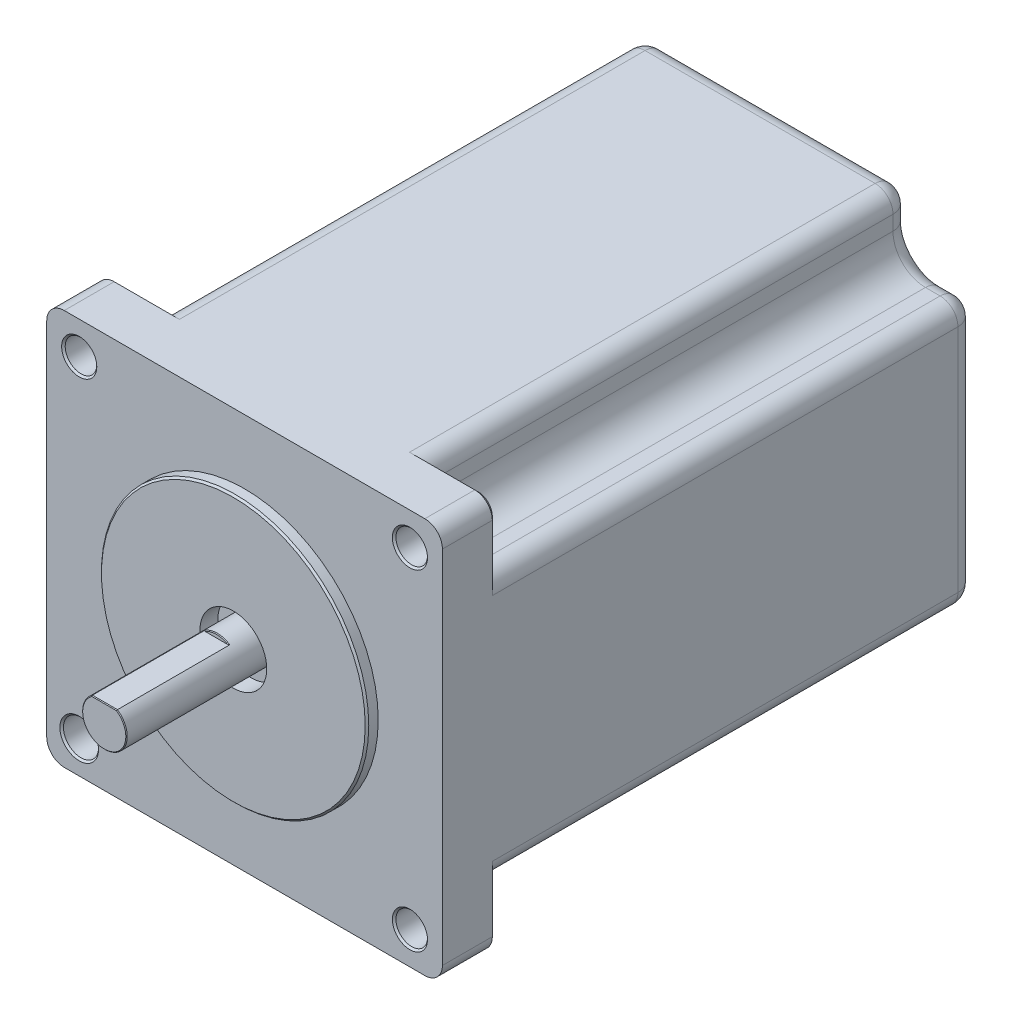
SolidWorks part; units mm, degrees
ref_plane "Front Plane" through (0, 0, 0) normal (0, 0, 1) x (1, 0, 0)
ref_plane "Top Plane" through (0, 0, 0) normal (0, 1, 0) x (1, 0, 0)
ref_plane "Right Plane" through (0, 0, 0) normal (1, 0, 0) x (0, 0, -1)
sketch "Sketch1" plane through (0, 0, 0) normal (0, 0, 1) x (1, 0, 0)
  line L0 (25.7, -28.2) -> (-25.7, -28.2)
  line L1 (-28.2, -25.7) -> (-28.2, 25.7)
  line L2 (-25.7, 28.2) -> (25.7, 28.2)
  line L3 (28.2, 25.7) -> (28.2, -25.7)
  line L4 (10.4502, 28.2) -> (10.4502, 25.35)
  line L5 (16.7502, 28.2) -> (16.7502, 25.35)
  line L6 (-10.4502, -28.2) -> (-10.4502, -25.35)
  line L7 (-16.7502, -28.2) -> (-16.7502, -25.35)
  line L8 (24.8128, -14.6733) -> (25.354, -14.1321)
  line L9 (24.2796, -14.1427) -> (24.8181, -13.6042)
  line L10 (28.2, -16.7502) -> (25.35, -16.7502)
  line L11 (23.8824, -14.8147) -> (24.1419, -15.0742)
  line L12 (28.2, -10.4502) -> (25.35, -10.4502)
  line L13 (-28.2, 16.7502) -> (-25.35, 16.7502)
  line L14 (-28.2, 10.4502) -> (-25.35, 10.4502)
  line L15 (26.4231, -14.1374) -> (25.8819, -13.5962)
  line L16 (25.8925, -14.6706) -> (25.354, -14.1321)
  line L17 (26.5644, -15.0678) -> (26.824, -14.8083)
  line L18 (25.8872, -12.5271) -> (25.346, -13.0683)
  line L19 (26.4204, -13.0577) -> (25.8819, -13.5962)
  line L20 (26.8176, -12.3858) -> (26.5581, -12.1262)
  line L21 (24.2769, -13.063) -> (24.8181, -13.6042)
  line L22 (24.8075, -12.5298) -> (25.346, -13.0683)
  line L23 (24.1356, -12.1326) -> (23.876, -12.3921)
  line L24 (-14.1374, -26.4231) -> (-13.5962, -25.8819)
  line L25 (-14.6706, -25.8925) -> (-14.1321, -25.354)
  line L26 (-15.0678, -26.5644) -> (-14.8083, -26.824)
  line L27 (-12.5271, -25.8872) -> (-13.0683, -25.346)
  line L28 (-13.0577, -26.4204) -> (-13.5962, -25.8819)
  line L29 (-12.3858, -26.8176) -> (-12.1262, -26.5581)
  line L30 (-13.063, -24.2769) -> (-13.6042, -24.8181)
  line L31 (-12.5298, -24.8075) -> (-13.0683, -25.346)
  line L32 (-12.1326, -24.1356) -> (-12.3921, -23.876)
  line L33 (-14.6733, -24.8128) -> (-14.1321, -25.354)
  line L34 (-14.1427, -24.2796) -> (-13.6042, -24.8181)
  line L35 (-14.8147, -23.8824) -> (-15.0742, -24.1419)
  line L36 (-25.8872, 12.5271) -> (-25.346, 13.0683)
  line L37 (-26.4204, 13.0577) -> (-25.8819, 13.5962)
  line L38 (-26.8176, 12.3858) -> (-26.5581, 12.1262)
  line L39 (-24.2769, 13.063) -> (-24.8181, 13.6042)
  line L40 (-24.8075, 12.5298) -> (-25.346, 13.0683)
  line L41 (-24.1356, 12.1326) -> (-23.876, 12.3921)
  line L42 (-24.8128, 14.6733) -> (-25.354, 14.1321)
  line L43 (-24.2796, 14.1427) -> (-24.8181, 13.6042)
  line L44 (-23.8824, 14.8147) -> (-24.1419, 15.0742)
  line L45 (-26.4231, 14.1374) -> (-25.8819, 13.5962)
  line L46 (-25.8925, 14.6706) -> (-25.354, 14.1321)
  line L47 (-26.5644, 15.0678) -> (-26.824, 14.8083)
  line L48 (13.063, 24.2769) -> (13.6042, 24.8181)
  line L49 (12.5298, 24.8075) -> (13.0683, 25.346)
  line L50 (12.1326, 24.1356) -> (12.3921, 23.876)
  line L51 (14.6733, 24.8128) -> (14.1321, 25.354)
  line L52 (14.1427, 24.2796) -> (13.6042, 24.8181)
  line L53 (14.8147, 23.8824) -> (15.0742, 24.1419)
  line L54 (14.1374, 26.4231) -> (13.5962, 25.8819)
  line L55 (14.6706, 25.8925) -> (14.1321, 25.354)
  line L56 (15.0678, 26.5644) -> (14.8083, 26.824)
  line L57 (12.5271, 25.8872) -> (13.0683, 25.346)
  line L58 (13.0577, 26.4204) -> (13.5962, 25.8819)
  line L59 (12.3858, 26.8176) -> (12.1262, 26.5581)
  line L60 (2.6694, -1.7014) -> (2.6694, 1.7574)
  line L61 (2.4712, -1.6418) -> (2.4712, 1.6978)
  line L62 (-5.066, -28.2) -> (5.066, -28.2)
  line L63 (5.066, -28.2) -> (5.938, -27.328)
  line L64 (-5.066, -28.2) -> (-5.938, -27.328)
  circle A0 centre (0, 0) radius 27.7884
  circle A1 centre (13.6002, 25.35) radius 2.2554
  arc A2 (-25.7, 28.2) -> (-28.2, 25.7) centre (-25.7, 25.7) ccw
  arc A3 (-28.2, -25.7) -> (-25.7, -28.2) centre (-25.7, -25.7) ccw
  arc A4 (25.7, -28.2) -> (28.2, -25.7) centre (25.7, -25.7) ccw
  arc A5 (28.2, 25.7) -> (25.7, 28.2) centre (25.7, 25.7) ccw
  circle A6 centre (-23.57, 23.57) radius 2.25
  circle A7 centre (23.57, 23.57) radius 2.25
  circle A8 centre (23.57, -23.57) radius 2.25
  arc A9 (10.4502, 25.35) -> (16.7502, 25.35) centre (13.6002, 25.35) ccw
  arc A10 (-10.4502, -25.35) -> (-16.7502, -25.35) centre (-13.6002, -25.35) ccw
  circle A11 centre (-13.6002, -25.35) radius 2.2554
  circle A12 centre (25.35, -13.6002) radius 2.2554
  arc A13 (25.35, -10.4502) -> (25.35, -16.7502) centre (25.35, -13.6002) ccw
  circle A14 centre (-25.35, 13.6002) radius 2.2554
  arc A15 (-25.35, 10.4502) -> (-25.35, 16.7502) centre (-25.35, 13.6002) ccw
  circle A16 centre (0, 0) radius 19.05
  arc A17 (2.6694, 1.7574) -> (2.6694, -1.7014) centre (0, 0.028) ccw
  circle A18 centre (-23.57, -23.57) radius 2.5
  arc A19 (24.2796, -14.1427) -> (23.8824, -14.8147) centre (25.548, -15.3459) ccw
  arc A20 (24.1419, -15.0742) -> (24.8128, -14.6733) centre (23.6033, -13.4109) ccw
  arc A21 (25.8925, -14.6706) -> (26.5644, -15.0678) centre (27.0957, -13.4022) ccw
  arc A22 (26.824, -14.8083) -> (26.4231, -14.1374) centre (25.1607, -15.3469) ccw
  arc A23 (26.4204, -13.0577) -> (26.8176, -12.3858) centre (25.152, -11.8545) ccw
  arc A24 (26.5581, -12.1262) -> (25.8872, -12.5271) centre (27.0967, -13.7895) ccw
  arc A25 (24.8075, -12.5298) -> (24.1356, -12.1326) centre (23.6043, -13.7982) ccw
  arc A26 (23.876, -12.3921) -> (24.2769, -13.063) centre (25.5393, -11.8535) ccw
  arc A27 (-14.6706, -25.8925) -> (-15.0678, -26.5644) centre (-13.4022, -27.0957) ccw
  arc A28 (-14.8083, -26.824) -> (-14.1374, -26.4231) centre (-15.3469, -25.1607) ccw
  arc A29 (-13.0577, -26.4204) -> (-12.3858, -26.8176) centre (-11.8545, -25.152) ccw
  arc A30 (-12.1262, -26.5581) -> (-12.5271, -25.8872) centre (-13.7895, -27.0967) ccw
  arc A31 (-12.5298, -24.8075) -> (-12.1326, -24.1356) centre (-13.7982, -23.6043) ccw
  arc A32 (-12.3921, -23.876) -> (-13.063, -24.2769) centre (-11.8535, -25.5393) ccw
  arc A33 (-14.1427, -24.2796) -> (-14.8147, -23.8824) centre (-15.3459, -25.548) ccw
  arc A34 (-15.0742, -24.1419) -> (-14.6733, -24.8128) centre (-13.4109, -23.6033) ccw
  arc A35 (-26.4204, 13.0577) -> (-26.8176, 12.3858) centre (-25.152, 11.8545) ccw
  arc A36 (-26.5581, 12.1262) -> (-25.8872, 12.5271) centre (-27.0967, 13.7895) ccw
  arc A37 (-24.8075, 12.5298) -> (-24.1356, 12.1326) centre (-23.6043, 13.7982) ccw
  arc A38 (-23.876, 12.3921) -> (-24.2769, 13.063) centre (-25.5393, 11.8535) ccw
  arc A39 (-24.2796, 14.1427) -> (-23.8824, 14.8147) centre (-25.548, 15.3459) ccw
  arc A40 (-24.1419, 15.0742) -> (-24.8128, 14.6733) centre (-23.6033, 13.4109) ccw
  arc A41 (-25.8925, 14.6706) -> (-26.5644, 15.0678) centre (-27.0957, 13.4022) ccw
  arc A42 (-26.824, 14.8083) -> (-26.4231, 14.1374) centre (-25.1607, 15.3469) ccw
  arc A43 (12.5298, 24.8075) -> (12.1326, 24.1356) centre (13.7982, 23.6043) ccw
  arc A44 (12.3921, 23.876) -> (13.063, 24.2769) centre (11.8535, 25.5393) ccw
  arc A45 (14.1427, 24.2796) -> (14.8147, 23.8824) centre (15.3459, 25.548) ccw
  arc A46 (15.0742, 24.1419) -> (14.6733, 24.8128) centre (13.4109, 23.6033) ccw
  arc A47 (14.6706, 25.8925) -> (15.0678, 26.5644) centre (13.4022, 27.0957) ccw
  arc A48 (14.8083, 26.824) -> (14.1374, 26.4231) centre (15.3469, 25.1607) ccw
  arc A49 (13.0577, 26.4204) -> (12.3858, 26.8176) centre (11.8545, 25.152) ccw
  arc A50 (12.1262, 26.5581) -> (12.5271, 25.8872) centre (13.7895, 27.0967) ccw
  circle A51 centre (0, 0) radius 4.5332
  arc A52 (2.4712, 1.6978) -> (2.4712, -1.6418) centre (0, 0.028) ccw
extrude "Extrude1" add sketch "Sketch1" along normal blind 7.62 contours L2 A5 L3 A4 L0 A3 L1 A2
sketch "Sketch2" plane through (0, 0, 7.62) normal (0, 0, 1) x (1, 0, 0)
  line L0 (25.7, -28.2) -> (-25.7, -28.2)
  line L1 (-28.2, -25.7) -> (-28.2, 25.7)
  line L2 (-25.7, 28.2) -> (25.7, 28.2)
  line L3 (28.2, 25.7) -> (28.2, -25.7)
  line L4 (10.4502, 28.2) -> (10.4502, 25.35)
  line L5 (16.7502, 28.2) -> (16.7502, 25.35)
  line L6 (-10.4502, -28.2) -> (-10.4502, -25.35)
  line L7 (-16.7502, -28.2) -> (-16.7502, -25.35)
  line L8 (24.8128, -14.6733) -> (25.354, -14.1321)
  line L9 (24.2796, -14.1427) -> (24.8181, -13.6042)
  line L10 (28.2, -16.7502) -> (25.35, -16.7502)
  line L11 (23.8824, -14.8147) -> (24.1419, -15.0742)
  line L12 (28.2, -10.4502) -> (25.35, -10.4502)
  line L13 (-28.2, 16.7502) -> (-25.35, 16.7502)
  line L14 (-28.2, 10.4502) -> (-25.35, 10.4502)
  line L15 (26.4231, -14.1374) -> (25.8819, -13.5962)
  line L16 (25.8925, -14.6706) -> (25.354, -14.1321)
  line L17 (26.5644, -15.0678) -> (26.824, -14.8083)
  line L18 (25.8872, -12.5271) -> (25.346, -13.0683)
  line L19 (26.4204, -13.0577) -> (25.8819, -13.5962)
  line L20 (26.8176, -12.3858) -> (26.5581, -12.1262)
  line L21 (24.2769, -13.063) -> (24.8181, -13.6042)
  line L22 (24.8075, -12.5298) -> (25.346, -13.0683)
  line L23 (24.1356, -12.1326) -> (23.876, -12.3921)
  line L24 (-14.1374, -26.4231) -> (-13.5962, -25.8819)
  line L25 (-14.6706, -25.8925) -> (-14.1321, -25.354)
  line L26 (-15.0678, -26.5644) -> (-14.8083, -26.824)
  line L27 (-12.5271, -25.8872) -> (-13.0683, -25.346)
  line L28 (-13.0577, -26.4204) -> (-13.5962, -25.8819)
  line L29 (-12.3858, -26.8176) -> (-12.1262, -26.5581)
  line L30 (-13.063, -24.2769) -> (-13.6042, -24.8181)
  line L31 (-12.5298, -24.8075) -> (-13.0683, -25.346)
  line L32 (-12.1326, -24.1356) -> (-12.3921, -23.876)
  line L33 (-14.6733, -24.8128) -> (-14.1321, -25.354)
  line L34 (-14.1427, -24.2796) -> (-13.6042, -24.8181)
  line L35 (-14.8147, -23.8824) -> (-15.0742, -24.1419)
  line L36 (-25.8872, 12.5271) -> (-25.346, 13.0683)
  line L37 (-26.4204, 13.0577) -> (-25.8819, 13.5962)
  line L38 (-26.8176, 12.3858) -> (-26.5581, 12.1262)
  line L39 (-24.2769, 13.063) -> (-24.8181, 13.6042)
  line L40 (-24.8075, 12.5298) -> (-25.346, 13.0683)
  line L41 (-24.1356, 12.1326) -> (-23.876, 12.3921)
  line L42 (-24.8128, 14.6733) -> (-25.354, 14.1321)
  line L43 (-24.2796, 14.1427) -> (-24.8181, 13.6042)
  line L44 (-23.8824, 14.8147) -> (-24.1419, 15.0742)
  line L45 (-26.4231, 14.1374) -> (-25.8819, 13.5962)
  line L46 (-25.8925, 14.6706) -> (-25.354, 14.1321)
  line L47 (-26.5644, 15.0678) -> (-26.824, 14.8083)
  line L48 (13.063, 24.2769) -> (13.6042, 24.8181)
  line L49 (12.5298, 24.8075) -> (13.0683, 25.346)
  line L50 (12.1326, 24.1356) -> (12.3921, 23.876)
  line L51 (14.6733, 24.8128) -> (14.1321, 25.354)
  line L52 (14.1427, 24.2796) -> (13.6042, 24.8181)
  line L53 (14.8147, 23.8824) -> (15.0742, 24.1419)
  line L54 (14.1374, 26.4231) -> (13.5962, 25.8819)
  line L55 (14.6706, 25.8925) -> (14.1321, 25.354)
  line L56 (15.0678, 26.5644) -> (14.8083, 26.824)
  line L57 (12.5271, 25.8872) -> (13.0683, 25.346)
  line L58 (13.0577, 26.4204) -> (13.5962, 25.8819)
  line L59 (12.3858, 26.8176) -> (12.1262, 26.5581)
  line L60 (2.6694, -1.7014) -> (2.6694, 1.7574)
  line L61 (2.4712, -1.6418) -> (2.4712, 1.6978)
  line L62 (-5.066, -28.2) -> (5.066, -28.2)
  line L63 (5.066, -28.2) -> (5.938, -27.328)
  line L64 (-5.066, -28.2) -> (-5.938, -27.328)
  circle A0 centre (13.6002, 25.35) radius 2.2554
  arc A1 (-25.7, 28.2) -> (-28.2, 25.7) centre (-25.7, 25.7) ccw
  arc A2 (-28.2, -25.7) -> (-25.7, -28.2) centre (-25.7, -25.7) ccw
  arc A3 (25.7, -28.2) -> (28.2, -25.7) centre (25.7, -25.7) ccw
  arc A4 (28.2, 25.7) -> (25.7, 28.2) centre (25.7, 25.7) ccw
  circle A5 centre (-23.57, 23.57) radius 2.25
  circle A6 centre (23.57, 23.57) radius 2.25
  circle A7 centre (23.57, -23.57) radius 2.25
  arc A8 (10.4502, 25.35) -> (16.7502, 25.35) centre (13.6002, 25.35) ccw
  arc A9 (-10.4502, -25.35) -> (-16.7502, -25.35) centre (-13.6002, -25.35) ccw
  circle A10 centre (-13.6002, -25.35) radius 2.2554
  circle A11 centre (25.35, -13.6002) radius 2.2554
  arc A12 (25.35, -10.4502) -> (25.35, -16.7502) centre (25.35, -13.6002) ccw
  circle A13 centre (-25.35, 13.6002) radius 2.2554
  arc A14 (-25.35, 10.4502) -> (-25.35, 16.7502) centre (-25.35, 13.6002) ccw
  circle A15 centre (0, 0) radius 19.05
  arc A16 (2.6694, 1.7574) -> (2.6694, -1.7014) centre (0, 0.028) ccw
  circle A17 centre (-23.57, -23.57) radius 2.5
  arc A18 (24.2796, -14.1427) -> (23.8824, -14.8147) centre (25.548, -15.3459) ccw
  arc A19 (24.1419, -15.0742) -> (24.8128, -14.6733) centre (23.6033, -13.4109) ccw
  arc A20 (25.8925, -14.6706) -> (26.5644, -15.0678) centre (27.0957, -13.4022) ccw
  arc A21 (26.824, -14.8083) -> (26.4231, -14.1374) centre (25.1607, -15.3469) ccw
  arc A22 (26.4204, -13.0577) -> (26.8176, -12.3858) centre (25.152, -11.8545) ccw
  arc A23 (26.5581, -12.1262) -> (25.8872, -12.5271) centre (27.0967, -13.7895) ccw
  arc A24 (24.8075, -12.5298) -> (24.1356, -12.1326) centre (23.6043, -13.7982) ccw
  arc A25 (23.876, -12.3921) -> (24.2769, -13.063) centre (25.5393, -11.8535) ccw
  arc A26 (-14.6706, -25.8925) -> (-15.0678, -26.5644) centre (-13.4022, -27.0957) ccw
  arc A27 (-14.8083, -26.824) -> (-14.1374, -26.4231) centre (-15.3469, -25.1607) ccw
  arc A28 (-13.0577, -26.4204) -> (-12.3858, -26.8176) centre (-11.8545, -25.152) ccw
  arc A29 (-12.1262, -26.5581) -> (-12.5271, -25.8872) centre (-13.7895, -27.0967) ccw
  arc A30 (-12.5298, -24.8075) -> (-12.1326, -24.1356) centre (-13.7982, -23.6043) ccw
  arc A31 (-12.3921, -23.876) -> (-13.063, -24.2769) centre (-11.8535, -25.5393) ccw
  arc A32 (-14.1427, -24.2796) -> (-14.8147, -23.8824) centre (-15.3459, -25.548) ccw
  arc A33 (-15.0742, -24.1419) -> (-14.6733, -24.8128) centre (-13.4109, -23.6033) ccw
  arc A34 (-26.4204, 13.0577) -> (-26.8176, 12.3858) centre (-25.152, 11.8545) ccw
  arc A35 (-26.5581, 12.1262) -> (-25.8872, 12.5271) centre (-27.0967, 13.7895) ccw
  arc A36 (-24.8075, 12.5298) -> (-24.1356, 12.1326) centre (-23.6043, 13.7982) ccw
  arc A37 (-23.876, 12.3921) -> (-24.2769, 13.063) centre (-25.5393, 11.8535) ccw
  arc A38 (-24.2796, 14.1427) -> (-23.8824, 14.8147) centre (-25.548, 15.3459) ccw
  arc A39 (-24.1419, 15.0742) -> (-24.8128, 14.6733) centre (-23.6033, 13.4109) ccw
  arc A40 (-25.8925, 14.6706) -> (-26.5644, 15.0678) centre (-27.0957, 13.4022) ccw
  arc A41 (-26.824, 14.8083) -> (-26.4231, 14.1374) centre (-25.1607, 15.3469) ccw
  arc A42 (12.5298, 24.8075) -> (12.1326, 24.1356) centre (13.7982, 23.6043) ccw
  arc A43 (12.3921, 23.876) -> (13.063, 24.2769) centre (11.8535, 25.5393) ccw
  arc A44 (14.1427, 24.2796) -> (14.8147, 23.8824) centre (15.3459, 25.548) ccw
  arc A45 (15.0742, 24.1419) -> (14.6733, 24.8128) centre (13.4109, 23.6033) ccw
  arc A46 (14.6706, 25.8925) -> (15.0678, 26.5644) centre (13.4022, 27.0957) ccw
  arc A47 (14.8083, 26.824) -> (14.1374, 26.4231) centre (15.3469, 25.1607) ccw
  arc A48 (13.0577, 26.4204) -> (12.3858, 26.8176) centre (11.8545, 25.152) ccw
  arc A49 (12.1262, 26.5581) -> (12.5271, 25.8872) centre (13.7895, 27.0967) ccw
  circle A50 centre (0, 0) radius 4.5332
  arc A51 (2.4712, 1.6978) -> (2.4712, -1.6418) centre (0, 0.028) ccw
extrude "Extrude2" cut sketch "Sketch2" against normal blind 7.62 contours A5
sketch "Sketch3" plane through (0, 0, 7.62) normal (0, 0, 1) x (1, 0, 0)
  line L0 (25.7, -28.2) -> (-25.7, -28.2)
  line L1 (-28.2, -25.7) -> (-28.2, 25.7)
  line L2 (-25.7, 28.2) -> (25.7, 28.2)
  line L3 (28.2, 25.7) -> (28.2, -25.7)
  line L4 (10.4502, 28.2) -> (10.4502, 25.35)
  line L5 (16.7502, 28.2) -> (16.7502, 25.35)
  line L6 (-10.4502, -28.2) -> (-10.4502, -25.35)
  line L7 (-16.7502, -28.2) -> (-16.7502, -25.35)
  line L8 (24.8128, -14.6733) -> (25.354, -14.1321)
  line L9 (24.2796, -14.1427) -> (24.8181, -13.6042)
  line L10 (28.2, -16.7502) -> (25.35, -16.7502)
  line L11 (23.8824, -14.8147) -> (24.1419, -15.0742)
  line L12 (28.2, -10.4502) -> (25.35, -10.4502)
  line L13 (-28.2, 16.7502) -> (-25.35, 16.7502)
  line L14 (-28.2, 10.4502) -> (-25.35, 10.4502)
  line L15 (26.4231, -14.1374) -> (25.8819, -13.5962)
  line L16 (25.8925, -14.6706) -> (25.354, -14.1321)
  line L17 (26.5644, -15.0678) -> (26.824, -14.8083)
  line L18 (25.8872, -12.5271) -> (25.346, -13.0683)
  line L19 (26.4204, -13.0577) -> (25.8819, -13.5962)
  line L20 (26.8176, -12.3858) -> (26.5581, -12.1262)
  line L21 (24.2769, -13.063) -> (24.8181, -13.6042)
  line L22 (24.8075, -12.5298) -> (25.346, -13.0683)
  line L23 (24.1356, -12.1326) -> (23.876, -12.3921)
  line L24 (-14.1374, -26.4231) -> (-13.5962, -25.8819)
  line L25 (-14.6706, -25.8925) -> (-14.1321, -25.354)
  line L26 (-15.0678, -26.5644) -> (-14.8083, -26.824)
  line L27 (-12.5271, -25.8872) -> (-13.0683, -25.346)
  line L28 (-13.0577, -26.4204) -> (-13.5962, -25.8819)
  line L29 (-12.3858, -26.8176) -> (-12.1262, -26.5581)
  line L30 (-13.063, -24.2769) -> (-13.6042, -24.8181)
  line L31 (-12.5298, -24.8075) -> (-13.0683, -25.346)
  line L32 (-12.1326, -24.1356) -> (-12.3921, -23.876)
  line L33 (-14.6733, -24.8128) -> (-14.1321, -25.354)
  line L34 (-14.1427, -24.2796) -> (-13.6042, -24.8181)
  line L35 (-14.8147, -23.8824) -> (-15.0742, -24.1419)
  line L36 (-25.8872, 12.5271) -> (-25.346, 13.0683)
  line L37 (-26.4204, 13.0577) -> (-25.8819, 13.5962)
  line L38 (-26.8176, 12.3858) -> (-26.5581, 12.1262)
  line L39 (-24.2769, 13.063) -> (-24.8181, 13.6042)
  line L40 (-24.8075, 12.5298) -> (-25.346, 13.0683)
  line L41 (-24.1356, 12.1326) -> (-23.876, 12.3921)
  line L42 (-24.8128, 14.6733) -> (-25.354, 14.1321)
  line L43 (-24.2796, 14.1427) -> (-24.8181, 13.6042)
  line L44 (-23.8824, 14.8147) -> (-24.1419, 15.0742)
  line L45 (-26.4231, 14.1374) -> (-25.8819, 13.5962)
  line L46 (-25.8925, 14.6706) -> (-25.354, 14.1321)
  line L47 (-26.5644, 15.0678) -> (-26.824, 14.8083)
  line L48 (13.063, 24.2769) -> (13.6042, 24.8181)
  line L49 (12.5298, 24.8075) -> (13.0683, 25.346)
  line L50 (12.1326, 24.1356) -> (12.3921, 23.876)
  line L51 (14.6733, 24.8128) -> (14.1321, 25.354)
  line L52 (14.1427, 24.2796) -> (13.6042, 24.8181)
  line L53 (14.8147, 23.8824) -> (15.0742, 24.1419)
  line L54 (14.1374, 26.4231) -> (13.5962, 25.8819)
  line L55 (14.6706, 25.8925) -> (14.1321, 25.354)
  line L56 (15.0678, 26.5644) -> (14.8083, 26.824)
  line L57 (12.5271, 25.8872) -> (13.0683, 25.346)
  line L58 (13.0577, 26.4204) -> (13.5962, 25.8819)
  line L59 (12.3858, 26.8176) -> (12.1262, 26.5581)
  line L60 (2.6694, -1.7014) -> (2.6694, 1.7574)
  line L61 (2.4712, -1.6418) -> (2.4712, 1.6978)
  line L62 (-5.066, -28.2) -> (5.066, -28.2)
  line L63 (5.066, -28.2) -> (5.938, -27.328)
  line L64 (-5.066, -28.2) -> (-5.938, -27.328)
  circle A0 centre (13.6002, 25.35) radius 2.2554
  arc A1 (-25.7, 28.2) -> (-28.2, 25.7) centre (-25.7, 25.7) ccw
  arc A2 (-28.2, -25.7) -> (-25.7, -28.2) centre (-25.7, -25.7) ccw
  arc A3 (25.7, -28.2) -> (28.2, -25.7) centre (25.7, -25.7) ccw
  arc A4 (28.2, 25.7) -> (25.7, 28.2) centre (25.7, 25.7) ccw
  circle A5 centre (-23.57, 23.57) radius 2.25
  circle A6 centre (23.57, 23.57) radius 2.25
  circle A7 centre (23.57, -23.57) radius 2.25
  arc A8 (10.4502, 25.35) -> (16.7502, 25.35) centre (13.6002, 25.35) ccw
  arc A9 (-10.4502, -25.35) -> (-16.7502, -25.35) centre (-13.6002, -25.35) ccw
  circle A10 centre (-13.6002, -25.35) radius 2.2554
  circle A11 centre (25.35, -13.6002) radius 2.2554
  arc A12 (25.35, -10.4502) -> (25.35, -16.7502) centre (25.35, -13.6002) ccw
  circle A13 centre (-25.35, 13.6002) radius 2.2554
  arc A14 (-25.35, 10.4502) -> (-25.35, 16.7502) centre (-25.35, 13.6002) ccw
  circle A15 centre (0, 0) radius 19.05
  arc A16 (2.6694, 1.7574) -> (2.6694, -1.7014) centre (0, 0.028) ccw
  circle A17 centre (-23.57, -23.57) radius 2.5
  arc A18 (24.2796, -14.1427) -> (23.8824, -14.8147) centre (25.548, -15.3459) ccw
  arc A19 (24.1419, -15.0742) -> (24.8128, -14.6733) centre (23.6033, -13.4109) ccw
  arc A20 (25.8925, -14.6706) -> (26.5644, -15.0678) centre (27.0957, -13.4022) ccw
  arc A21 (26.824, -14.8083) -> (26.4231, -14.1374) centre (25.1607, -15.3469) ccw
  arc A22 (26.4204, -13.0577) -> (26.8176, -12.3858) centre (25.152, -11.8545) ccw
  arc A23 (26.5581, -12.1262) -> (25.8872, -12.5271) centre (27.0967, -13.7895) ccw
  arc A24 (24.8075, -12.5298) -> (24.1356, -12.1326) centre (23.6043, -13.7982) ccw
  arc A25 (23.876, -12.3921) -> (24.2769, -13.063) centre (25.5393, -11.8535) ccw
  arc A26 (-14.6706, -25.8925) -> (-15.0678, -26.5644) centre (-13.4022, -27.0957) ccw
  arc A27 (-14.8083, -26.824) -> (-14.1374, -26.4231) centre (-15.3469, -25.1607) ccw
  arc A28 (-13.0577, -26.4204) -> (-12.3858, -26.8176) centre (-11.8545, -25.152) ccw
  arc A29 (-12.1262, -26.5581) -> (-12.5271, -25.8872) centre (-13.7895, -27.0967) ccw
  arc A30 (-12.5298, -24.8075) -> (-12.1326, -24.1356) centre (-13.7982, -23.6043) ccw
  arc A31 (-12.3921, -23.876) -> (-13.063, -24.2769) centre (-11.8535, -25.5393) ccw
  arc A32 (-14.1427, -24.2796) -> (-14.8147, -23.8824) centre (-15.3459, -25.548) ccw
  arc A33 (-15.0742, -24.1419) -> (-14.6733, -24.8128) centre (-13.4109, -23.6033) ccw
  arc A34 (-26.4204, 13.0577) -> (-26.8176, 12.3858) centre (-25.152, 11.8545) ccw
  arc A35 (-26.5581, 12.1262) -> (-25.8872, 12.5271) centre (-27.0967, 13.7895) ccw
  arc A36 (-24.8075, 12.5298) -> (-24.1356, 12.1326) centre (-23.6043, 13.7982) ccw
  arc A37 (-23.876, 12.3921) -> (-24.2769, 13.063) centre (-25.5393, 11.8535) ccw
  arc A38 (-24.2796, 14.1427) -> (-23.8824, 14.8147) centre (-25.548, 15.3459) ccw
  arc A39 (-24.1419, 15.0742) -> (-24.8128, 14.6733) centre (-23.6033, 13.4109) ccw
  arc A40 (-25.8925, 14.6706) -> (-26.5644, 15.0678) centre (-27.0957, 13.4022) ccw
  arc A41 (-26.824, 14.8083) -> (-26.4231, 14.1374) centre (-25.1607, 15.3469) ccw
  arc A42 (12.5298, 24.8075) -> (12.1326, 24.1356) centre (13.7982, 23.6043) ccw
  arc A43 (12.3921, 23.876) -> (13.063, 24.2769) centre (11.8535, 25.5393) ccw
  arc A44 (14.1427, 24.2796) -> (14.8147, 23.8824) centre (15.3459, 25.548) ccw
  arc A45 (15.0742, 24.1419) -> (14.6733, 24.8128) centre (13.4109, 23.6033) ccw
  arc A46 (14.6706, 25.8925) -> (15.0678, 26.5644) centre (13.4022, 27.0957) ccw
  arc A47 (14.8083, 26.824) -> (14.1374, 26.4231) centre (15.3469, 25.1607) ccw
  arc A48 (13.0577, 26.4204) -> (12.3858, 26.8176) centre (11.8545, 25.152) ccw
  arc A49 (12.1262, 26.5581) -> (12.5271, 25.8872) centre (13.7895, 27.0967) ccw
  circle A50 centre (0, 0) radius 4.5332
  arc A51 (2.4712, 1.6978) -> (2.4712, -1.6418) centre (0, 0.028) ccw
extrude "Extrude3" cut sketch "Sketch3" against normal blind 7.62 contours A6 | A17 | A7
sketch "Sketch5" plane through (0, 0, 0) normal (0, 0, 1) x (1, 0, 0)
  line L0 (10.4502, 28.2) -> (10.4502, 25.35)
  line L1 (16.7502, 28.2) -> (16.7502, 25.35)
  line L2 (-10.4502, -28.2) -> (-10.4502, -25.35)
  line L3 (-16.7502, -28.2) -> (-16.7502, -25.35)
  line L4 (24.8128, -14.6733) -> (25.354, -14.1321)
  line L5 (24.2796, -14.1427) -> (24.8181, -13.6042)
  line L6 (28.2, -16.7502) -> (25.35, -16.7502)
  line L7 (23.8824, -14.8147) -> (24.1419, -15.0742)
  line L8 (28.2, -10.4502) -> (25.35, -10.4502)
  line L9 (-28.2, 16.7502) -> (-25.35, 16.7502)
  line L10 (-28.2, 10.4502) -> (-25.35, 10.4502)
  line L11 (26.4231, -14.1374) -> (25.8819, -13.5962)
  line L12 (25.8925, -14.6706) -> (25.354, -14.1321)
  line L13 (26.5644, -15.0678) -> (26.824, -14.8083)
  line L14 (25.8872, -12.5271) -> (25.346, -13.0683)
  line L15 (26.4204, -13.0577) -> (25.8819, -13.5962)
  line L16 (26.8176, -12.3858) -> (26.5581, -12.1262)
  line L17 (24.2769, -13.063) -> (24.8181, -13.6042)
  line L18 (24.8075, -12.5298) -> (25.346, -13.0683)
  line L19 (24.1356, -12.1326) -> (23.876, -12.3921)
  line L20 (-14.1374, -26.4231) -> (-13.5962, -25.8819)
  line L21 (-14.6706, -25.8925) -> (-14.1321, -25.354)
  line L22 (-15.0678, -26.5644) -> (-14.8083, -26.824)
  line L23 (-12.5271, -25.8872) -> (-13.0683, -25.346)
  line L24 (-13.0577, -26.4204) -> (-13.5962, -25.8819)
  line L25 (-12.3858, -26.8176) -> (-12.1262, -26.5581)
  line L26 (-13.063, -24.2769) -> (-13.6042, -24.8181)
  line L27 (-12.5298, -24.8075) -> (-13.0683, -25.346)
  line L28 (-12.1326, -24.1356) -> (-12.3921, -23.876)
  line L29 (-14.6733, -24.8128) -> (-14.1321, -25.354)
  line L30 (-14.1427, -24.2796) -> (-13.6042, -24.8181)
  line L31 (-14.8147, -23.8824) -> (-15.0742, -24.1419)
  line L32 (-25.8872, 12.5271) -> (-25.346, 13.0683)
  line L33 (-26.4204, 13.0577) -> (-25.8819, 13.5962)
  line L34 (-26.8176, 12.3858) -> (-26.5581, 12.1262)
  line L35 (-24.2769, 13.063) -> (-24.8181, 13.6042)
  line L36 (-24.8075, 12.5298) -> (-25.346, 13.0683)
  line L37 (-24.1356, 12.1326) -> (-23.876, 12.3921)
  line L38 (-24.8128, 14.6733) -> (-25.354, 14.1321)
  line L39 (-24.2796, 14.1427) -> (-24.8181, 13.6042)
  line L40 (-23.8824, 14.8147) -> (-24.1419, 15.0742)
  line L41 (-26.4231, 14.1374) -> (-25.8819, 13.5962)
  line L42 (-25.8925, 14.6706) -> (-25.354, 14.1321)
  line L43 (-26.5644, 15.0678) -> (-26.824, 14.8083)
  line L44 (13.063, 24.2769) -> (13.6042, 24.8181)
  line L45 (12.5298, 24.8075) -> (13.0683, 25.346)
  line L46 (12.1326, 24.1356) -> (12.3921, 23.876)
  line L47 (14.6733, 24.8128) -> (14.1321, 25.354)
  line L48 (14.1427, 24.2796) -> (13.6042, 24.8181)
  line L49 (14.8147, 23.8824) -> (15.0742, 24.1419)
  line L50 (14.1374, 26.4231) -> (13.5962, 25.8819)
  line L51 (14.6706, 25.8925) -> (14.1321, 25.354)
  line L52 (15.0678, 26.5644) -> (14.8083, 26.824)
  line L53 (12.5271, 25.8872) -> (13.0683, 25.346)
  line L54 (13.0577, 26.4204) -> (13.5962, 25.8819)
  line L55 (12.3858, 26.8176) -> (12.1262, 26.5581)
  line L56 (2.6694, -1.7014) -> (2.6694, 1.7574)
  line L57 (2.4712, -1.6418) -> (2.4712, 1.6978)
  line L58 (-5.066, -28.2) -> (5.066, -28.2)
  line L59 (5.066, -28.2) -> (5.938, -27.328)
  line L60 (-5.066, -28.2) -> (-5.938, -27.328)
  circle A0 centre (13.6002, 25.35) radius 2.2554
  arc A1 (-25.7, 28.2) -> (-28.2, 25.7) centre (-25.7, 25.7) ccw
  arc A2 (-28.2, -25.7) -> (-25.7, -28.2) centre (-25.7, -25.7) ccw
  arc A3 (25.7, -28.2) -> (28.2, -25.7) centre (25.7, -25.7) ccw
  arc A4 (28.2, 25.7) -> (25.7, 28.2) centre (25.7, 25.7) ccw
  circle A5 centre (-23.57, 23.57) radius 2.25
  circle A6 centre (23.57, 23.57) radius 2.25
  circle A7 centre (23.57, -23.57) radius 2.25
  arc A8 (10.4502, 25.35) -> (16.7502, 25.35) centre (13.6002, 25.35) ccw
  arc A9 (-10.4502, -25.35) -> (-16.7502, -25.35) centre (-13.6002, -25.35) ccw
  circle A10 centre (-13.6002, -25.35) radius 2.2554
  circle A11 centre (25.35, -13.6002) radius 2.2554
  arc A12 (25.35, -10.4502) -> (25.35, -16.7502) centre (25.35, -13.6002) ccw
  circle A13 centre (-25.35, 13.6002) radius 2.2554
  arc A14 (-25.35, 10.4502) -> (-25.35, 16.7502) centre (-25.35, 13.6002) ccw
  circle A15 centre (0, 0) radius 19.05
  arc A16 (2.6694, 1.7574) -> (2.6694, -1.7014) centre (0, 0.028) ccw
  circle A17 centre (-23.57, -23.57) radius 2.5
  arc A18 (24.2796, -14.1427) -> (23.8824, -14.8147) centre (25.548, -15.3459) ccw
  arc A19 (24.1419, -15.0742) -> (24.8128, -14.6733) centre (23.6033, -13.4109) ccw
  arc A20 (25.8925, -14.6706) -> (26.5644, -15.0678) centre (27.0957, -13.4022) ccw
  arc A21 (26.824, -14.8083) -> (26.4231, -14.1374) centre (25.1607, -15.3469) ccw
  arc A22 (26.4204, -13.0577) -> (26.8176, -12.3858) centre (25.152, -11.8545) ccw
  arc A23 (26.5581, -12.1262) -> (25.8872, -12.5271) centre (27.0967, -13.7895) ccw
  arc A24 (24.8075, -12.5298) -> (24.1356, -12.1326) centre (23.6043, -13.7982) ccw
  arc A25 (23.876, -12.3921) -> (24.2769, -13.063) centre (25.5393, -11.8535) ccw
  arc A26 (-14.6706, -25.8925) -> (-15.0678, -26.5644) centre (-13.4022, -27.0957) ccw
  arc A27 (-14.8083, -26.824) -> (-14.1374, -26.4231) centre (-15.3469, -25.1607) ccw
  arc A28 (-13.0577, -26.4204) -> (-12.3858, -26.8176) centre (-11.8545, -25.152) ccw
  arc A29 (-12.1262, -26.5581) -> (-12.5271, -25.8872) centre (-13.7895, -27.0967) ccw
  arc A30 (-12.5298, -24.8075) -> (-12.1326, -24.1356) centre (-13.7982, -23.6043) ccw
  arc A31 (-12.3921, -23.876) -> (-13.063, -24.2769) centre (-11.8535, -25.5393) ccw
  arc A32 (-14.1427, -24.2796) -> (-14.8147, -23.8824) centre (-15.3459, -25.548) ccw
  arc A33 (-15.0742, -24.1419) -> (-14.6733, -24.8128) centre (-13.4109, -23.6033) ccw
  arc A34 (-26.4204, 13.0577) -> (-26.8176, 12.3858) centre (-25.152, 11.8545) ccw
  arc A35 (-26.5581, 12.1262) -> (-25.8872, 12.5271) centre (-27.0967, 13.7895) ccw
  arc A36 (-24.8075, 12.5298) -> (-24.1356, 12.1326) centre (-23.6043, 13.7982) ccw
  arc A37 (-23.876, 12.3921) -> (-24.2769, 13.063) centre (-25.5393, 11.8535) ccw
  arc A38 (-24.2796, 14.1427) -> (-23.8824, 14.8147) centre (-25.548, 15.3459) ccw
  arc A39 (-24.1419, 15.0742) -> (-24.8128, 14.6733) centre (-23.6033, 13.4109) ccw
  arc A40 (-25.8925, 14.6706) -> (-26.5644, 15.0678) centre (-27.0957, 13.4022) ccw
  arc A41 (-26.824, 14.8083) -> (-26.4231, 14.1374) centre (-25.1607, 15.3469) ccw
  arc A42 (12.5298, 24.8075) -> (12.1326, 24.1356) centre (13.7982, 23.6043) ccw
  arc A43 (12.3921, 23.876) -> (13.063, 24.2769) centre (11.8535, 25.5393) ccw
  arc A44 (14.1427, 24.2796) -> (14.8147, 23.8824) centre (15.3459, 25.548) ccw
  arc A45 (15.0742, 24.1419) -> (14.6733, 24.8128) centre (13.4109, 23.6033) ccw
  arc A46 (14.6706, 25.8925) -> (15.0678, 26.5644) centre (13.4022, 27.0957) ccw
  arc A47 (14.8083, 26.824) -> (14.1374, 26.4231) centre (15.3469, 25.1607) ccw
  arc A48 (13.0577, 26.4204) -> (12.3858, 26.8176) centre (11.8545, 25.152) ccw
  arc A49 (12.1262, 26.5581) -> (12.5271, 25.8872) centre (13.7895, 27.0967) ccw
  circle A50 centre (0, 0) radius 4.5332
  arc A51 (2.4712, 1.6978) -> (2.4712, -1.6418) centre (0, 0.028) ccw
extrude "Extrude5" add sketch "Sketch5" along normal blind 9.222 contours A15
sketch "Sketch6" plane through (0, 0, 0) normal (0, 0, 1) x (1, 0, 0)
  line L0 (10.4502, 28.2) -> (10.4502, 25.35)
  line L1 (16.7502, 28.2) -> (16.7502, 25.35)
  line L4 (24.8128, -14.6733) -> (25.354, -14.1321)
  line L5 (24.2796, -14.1427) -> (24.8181, -13.6042)
  line L6 (28.2, -16.7502) -> (25.35, -16.7502)
  line L7 (23.8824, -14.8147) -> (24.1419, -15.0742)
  line L8 (28.2, -10.4502) -> (25.35, -10.4502)
  line L11 (26.4231, -14.1374) -> (25.8819, -13.5962)
  line L12 (25.8925, -14.6706) -> (25.354, -14.1321)
  line L13 (26.5644, -15.0678) -> (26.824, -14.8083)
  line L14 (25.8872, -12.5271) -> (25.346, -13.0683)
  line L15 (26.4204, -13.0577) -> (25.8819, -13.5962)
  line L16 (26.8176, -12.3858) -> (26.5581, -12.1262)
  line L17 (24.2769, -13.063) -> (24.8181, -13.6042)
  line L18 (24.8075, -12.5298) -> (25.346, -13.0683)
  line L19 (24.1356, -12.1326) -> (23.876, -12.3921)
  line L20 (-14.1374, -26.4231) -> (-13.5962, -25.8819)
  line L21 (-14.6706, -25.8925) -> (-14.1321, -25.354)
  line L22 (-15.0678, -26.5644) -> (-14.8083, -26.824)
  line L24 (-13.0577, -26.4204) -> (-13.5962, -25.8819)
  line L26 (-13.063, -24.2769) -> (-13.6042, -24.8181)
  line L27 (-12.5298, -24.8075) -> (-13.0683, -25.346)
  line L28 (-12.1326, -24.1356) -> (-12.3921, -23.876)
  line L29 (-14.6733, -24.8128) -> (-14.1321, -25.354)
  line L30 (-14.1427, -24.2796) -> (-13.6042, -24.8181)
  line L31 (-14.8147, -23.8824) -> (-15.0742, -24.1419)
  line L44 (13.063, 24.2769) -> (13.6042, 24.8181)
  line L45 (12.5298, 24.8075) -> (13.0683, 25.346)
  line L46 (12.1326, 24.1356) -> (12.3921, 23.876)
  line L47 (14.6733, 24.8128) -> (14.1321, 25.354)
  line L48 (14.1427, 24.2796) -> (13.6042, 24.8181)
  line L49 (14.8147, 23.8824) -> (15.0742, 24.1419)
  line L50 (14.1374, 26.4231) -> (13.5962, 25.8819)
  line L51 (14.6706, 25.8925) -> (14.1321, 25.354)
  line L52 (15.0678, 26.5644) -> (14.8083, 26.824)
  line L53 (12.5271, 25.8872) -> (13.0683, 25.346)
  line L54 (13.0577, 26.4204) -> (13.5962, 25.8819)
  line L55 (12.3858, 26.8176) -> (12.1262, 26.5581)
  line L56 (2.6694, -1.7014) -> (2.6694, 1.7574)
  line L57 (2.4712, -1.6418) -> (2.4712, 1.6978)
  line L58 (-5.066, -28.2) -> (5.066, -28.2)
  line L59 (5.066, -28.2) -> (5.938, -27.328)
  line L60 (-5.066, -28.2) -> (-5.938, -27.328)
  line L61 (18.94, 23.57) -> (18.94, 28.2)
  line L62 (-25.7, 28.2) -> (25.7, 28.2) construction
  line L63 (23.57, 18.94) -> (28.2, 18.94)
  line L64 (28.2, 25.7) -> (28.2, -25.7) construction
  line L65 (23.57, -18.94) -> (28.2, -18.94)
  line L66 (28.2, 25.7) -> (28.2, -25.7) construction
  line L67 (28.2, -18.94) -> (28.2, 18.94)
  line L68 (18.94, -23.57) -> (18.94, -28.2)
  line L69 (25.7, -28.2) -> (-25.7, -28.2) construction
  line L70 (18.94, -28.2) -> (-18.94, -28.2)
  line L71 (-18.94, -28.2) -> (-18.94, -23.57)
  line L72 (-23.57, -18.94) -> (-28.2, -18.94)
  line L73 (-28.2, -25.7) -> (-28.2, 25.7) construction
  line L74 (-28.2, -18.94) -> (-28.2, 18.94)
  line L75 (-28.2, 18.94) -> (-23.57, 18.94)
  line L76 (-18.94, 23.57) -> (-18.94, 28.2)
  line L77 (-25.7, 28.2) -> (25.7, 28.2) construction
  line L78 (-18.94, 28.2) -> (18.94, 28.2)
  circle A0 centre (13.6002, 25.35) radius 2.2554
  arc A4 (28.2, 25.7) -> (25.7, 28.2) centre (25.7, 25.7) ccw
  circle A5 centre (-23.57, 23.57) radius 2.25
  circle A6 centre (23.57, 23.57) radius 2.25
  circle A7 centre (23.57, -23.57) radius 2.25
  arc A8 (10.4502, 25.35) -> (16.7502, 25.35) centre (13.6002, 25.35) ccw
  arc A9 (-10.4502, -25.35) -> (-16.7502, -25.35) centre (-13.6002, -25.35) ccw
  circle A11 centre (25.35, -13.6002) radius 2.2554
  arc A12 (25.35, -10.4502) -> (25.35, -16.7502) centre (25.35, -13.6002) ccw
  circle A15 centre (0, 0) radius 19.05
  arc A16 (2.6694, 1.7574) -> (2.6694, -1.7014) centre (0, 0.028) ccw
  circle A17 centre (-23.57, -23.57) radius 2.5
  arc A18 (24.2796, -14.1427) -> (23.8824, -14.8147) centre (25.548, -15.3459) ccw
  arc A19 (24.1419, -15.0742) -> (24.8128, -14.6733) centre (23.6033, -13.4109) ccw
  arc A20 (25.8925, -14.6706) -> (26.5644, -15.0678) centre (27.0957, -13.4022) ccw
  arc A21 (26.824, -14.8083) -> (26.4231, -14.1374) centre (25.1607, -15.3469) ccw
  arc A22 (26.4204, -13.0577) -> (26.8176, -12.3858) centre (25.152, -11.8545) ccw
  arc A23 (26.5581, -12.1262) -> (25.8872, -12.5271) centre (27.0967, -13.7895) ccw
  arc A24 (24.8075, -12.5298) -> (24.1356, -12.1326) centre (23.6043, -13.7982) ccw
  arc A25 (23.876, -12.3921) -> (24.2769, -13.063) centre (25.5393, -11.8535) ccw
  arc A26 (-14.6706, -25.8925) -> (-15.0678, -26.5644) centre (-13.4022, -27.0957) ccw
  arc A27 (-14.8083, -26.824) -> (-14.1374, -26.4231) centre (-15.3469, -25.1607) ccw
  arc A29 (-12.1262, -26.5581) -> (-12.5271, -25.8872) centre (-13.7895, -27.0967) ccw
  arc A30 (-12.5298, -24.8075) -> (-12.1326, -24.1356) centre (-13.7982, -23.6043) ccw
  arc A31 (-12.3921, -23.876) -> (-13.063, -24.2769) centre (-11.8535, -25.5393) ccw
  arc A32 (-14.1427, -24.2796) -> (-14.8147, -23.8824) centre (-15.3459, -25.548) ccw
  arc A33 (-15.0742, -24.1419) -> (-14.6733, -24.8128) centre (-13.4109, -23.6033) ccw
  arc A37 (-23.876, 12.3921) -> (-24.2769, 13.063) centre (-25.5393, 11.8535) ccw
  arc A42 (12.5298, 24.8075) -> (12.1326, 24.1356) centre (13.7982, 23.6043) ccw
  arc A43 (12.3921, 23.876) -> (13.063, 24.2769) centre (11.8535, 25.5393) ccw
  arc A44 (14.1427, 24.2796) -> (14.8147, 23.8824) centre (15.3459, 25.548) ccw
  arc A45 (15.0742, 24.1419) -> (14.6733, 24.8128) centre (13.4109, 23.6033) ccw
  arc A46 (14.6706, 25.8925) -> (15.0678, 26.5644) centre (13.4022, 27.0957) ccw
  arc A47 (14.8083, 26.824) -> (14.1374, 26.4231) centre (15.3469, 25.1607) ccw
  arc A48 (13.0577, 26.4204) -> (12.3858, 26.8176) centre (11.8545, 25.152) ccw
  arc A49 (12.1262, 26.5581) -> (12.5271, 25.8872) centre (13.7895, 27.0967) ccw
  circle A50 centre (0, 0) radius 4.5332
  arc A51 (2.4712, 1.6978) -> (2.4712, -1.6418) centre (0, 0.028) ccw
  arc A52 (18.94, 23.57) -> (23.57, 18.94) centre (23.57, 23.57) ccw
  arc A53 (-23.57, 18.94) -> (-18.94, 23.57) centre (-23.57, 23.57) ccw
  arc A54 (-18.94, -23.57) -> (-23.57, -18.94) centre (-23.57, -23.57) ccw
  arc A55 (23.57, -18.94) -> (18.94, -23.57) centre (23.57, -23.57) ccw
extrude "Extrude7" add sketch "Sketch6" against normal blind 68.4
fillet "Fillet1" radius 2.54 24 edges at (20.2961, 20.2961, -68.4) (18.94, 25.885, -68.4) (0, 28.2, -68.4) (-18.94, 25.885, -68.4) (-20.2961, 20.2961, -68.4) (-25.885, 18.94, -68.4) (-28.2, 0, -68.4) (-25.885, -18.94, -68.4) (-20.2961, -20.2961, -68.4) (-18.94, -25.885, -68.4) (0, -28.2, -68.4) (18.94, -25.885, -68.4) (20.2961, -20.2961, -68.4) (25.885, -18.94, -68.4) (28.2, 0, -68.4) (25.885, 18.94, -68.4)
chamfer "Chamfer1" distance 0.508 angle 45 3 edges at (27.4678, 27.4678, 0)
chamfer "Chamfer2" distance 0.508 angle 45 3 edges at (-27.4678, -27.4678, 0)
sketch "Sketch8" plane through (0, 0, -68.4) normal (0, 0, -1) x (-1, 0, 0)
  circle A0 centre (0, 0) radius 5.8354
extrude "Extrude9" cut sketch "Sketch8" against normal blind 2.54
chamfer "Chamfer6" distance 0.254 angle 45 1 edges at (-5.8354, 0, -68.4)
chamfer "Chamfer7" distance 0.508 angle 45 3 edges at (27.4678, -27.4678, 0)
chamfer "Chamfer8" distance 0.508 angle 45 3 edges at (-27.4678, 27.4678, 0)
sketch "Sketch9" plane through (0, 0, 9.222) normal (0, 0, 1) x (1, 0, 0)
  circle A0 centre (0, 0) radius 4.7625
  dimension "D1" = 9.525
extrude "Cut-Extrude1" cut sketch "Sketch9" against normal blind 2.54
sketch "Sketch10" plane through (0, 0, 6.682) normal (0, 0, 1) x (1, 0, 0)
  circle A0 centre (0, 0) radius 3.175
extrude "Boss-Extrude1" add sketch "Sketch10" along normal blind 20.94
sketch "Sketch11" plane through (0, 0, -65.86) normal (0, 0, -1) x (-1, 0, 0)
  circle A0 centre (0, 0) radius 3.175
extrude "Boss-Extrude2" add sketch "Sketch11" along normal blind 17.538
chamfer "Chamfer9" distance 0.254 angle 45 1 edges at (19.05, 0, 9.222)
chamfer "Chamfer10" distance 0.254 angle 45 4 edges at (-21.32, 23.57, 7.62) (-21.07, -23.57, 7.62) (25.82, -23.57, 7.62) (25.82, 23.57, 7.62)
chamfer "Chamfer11" distance 0.254 angle 45 4 edges at (25.82, 23.57, 0) (25.82, -23.57, 0) (-21.32, 23.57, 0) (-21.07, -23.57, 0)
sketch "Sketch12" plane through (0, 0, 27.622) normal (0, 0, 1) x (1, 0, 0)
  line L1 (-3.9068, 6.1042) -> (4.63, 6.1042)
  line L2 (-3.9068, 6.1042) -> (-3.9068, 2.625)
  line L3 (-3.9068, 2.625) -> (4.63, 2.625)
  line L4 (4.63, 6.1042) -> (4.63, 2.625)
extrude "Cut-Extrude2" cut sketch "Sketch12" against normal blind 16
chamfer "Chamfer12" distance 0.1 angle 45 3 edges at (0, 3.175, 11.622) (0, -3.175, 27.622) (0, 2.625, 27.622)
sketch "Sketch13" plane through (0, 0, -83.398) normal (0, 0, -1) x (-1, 0, 0)
  line L1 (-5.9072, 7.0143) -> (6.2212, 7.0143)
  line L2 (-5.9072, 7.0143) -> (-5.9072, 2.625)
  line L3 (-5.9072, 2.625) -> (6.2212, 2.625)
  line L4 (6.2212, 7.0143) -> (6.2212, 2.625)
extrude "Cut-Extrude3" cut sketch "Sketch13" against normal blind 14
chamfer "Chamfer13" distance 0.1 angle 45 3 edges at (0, 3.175, -69.398) (0, 2.625, -83.398) (0, -3.175, -83.398)
